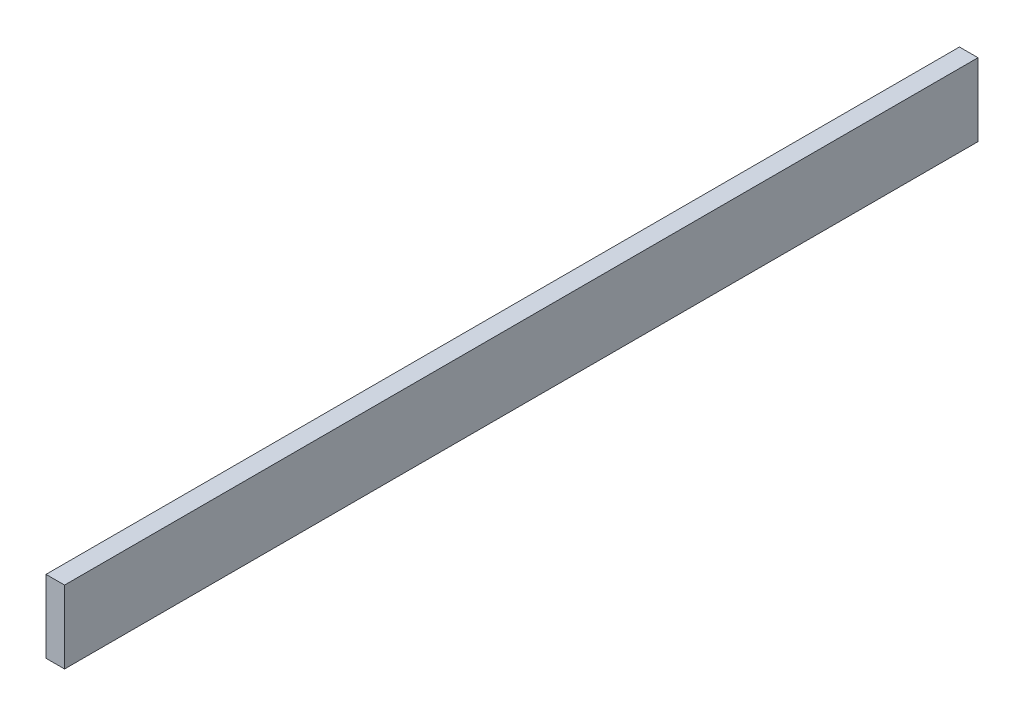
SolidWorks part; units mm, degrees
ref_plane "Front Plane" through (0, 0, 0) normal (0, 0, 1) x (1, 0, 0)
ref_plane "Top Plane" through (0, 0, 0) normal (0, 1, 0) x (1, 0, 0)
ref_plane "Right Plane" through (0, 0, 0) normal (1, 0, 0) x (0, 0, -1)
sketch "Sketch1" plane through (0, 0, 0) normal (0, 0, 1) x (1, 0, 0)
  line L1 (10.16, 39.7933) -> (-10.16, 39.7933)
  line L2 (10.16, 39.7933) -> (10.16, -39.7933)
  line L3 (10.16, -39.7933) -> (-10.16, -39.7933)
  line L4 (-10.16, 39.7933) -> (-10.16, -39.7933)
  line L5 (10.16, 39.7933) -> (-10.16, -39.7933) construction
  line L6 (10.16, -39.7933) -> (-10.16, 39.7933) construction
  point P0 (0, 0)
  dimension "D1" = 20.32
  dimension "D2" = 79.5867
extrude "Boss-Extrude1" add sketch "Sketch1" along normal blind 1000
